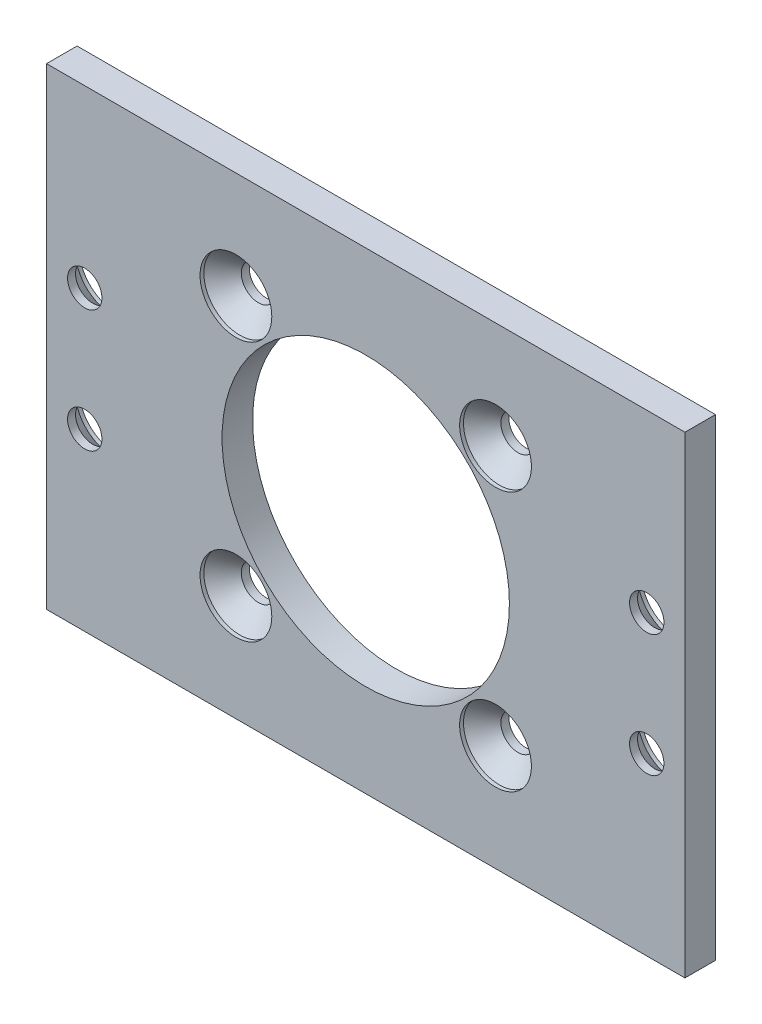
SolidWorks part; units mm, degrees
ref_plane "Plan de face" through (0, 0, 0) normal (0, 0, 1) x (1, 0, 0)
ref_plane "Plan de dessus" through (0, 0, 0) normal (0, 1, 0) x (1, 0, 0)
ref_plane "Plan de droite" through (0, 0, 0) normal (1, 0, 0) x (0, 0, -1)
sketch "Esquisse1" plane through (0, 0, 0) normal (0, 0, 1) x (1, 0, 0)
  line L0 (41.8, -30.95) -> (-41.8, -30.95)
  line L1 (41.8, -30.95) -> (41.8, 30.95)
  line L2 (-41.8, -30.95) -> (-41.8, 30.95)
  line L3 (41.8, 30.95) -> (-41.8, 30.95)
  line L4 (41.8, -30.95) -> (-41.8, 30.95) construction
  circle A0 centre (0, 0) radius 18.8138
  point P7 (0, 0)
  dimension "D1" = 83.6
  dimension "D2" = 61.9
extrude "Boss.-Extru.1" add sketch "Esquisse1" along normal blind 4
sketch "Esquisse2" plane through (0, 0, 4) normal (0, 0, 1) x (1, 0, 0)
  line L0 (17, -17) -> (-17, -17) construction
  line L1 (17, -17) -> (17, 17) construction
  line L2 (-17, -17) -> (-17, 17) construction
  line L3 (17, 17) -> (-17, 17) construction
  line L8 (-17, 17) -> (17, -17) construction
  point P12 (0, 0)
  dimension "D1" = 34
hole_wizard "Fraisage pour vis à tête fraisée M41" positions "Esquisse3" profile "Esquisse4" countersink size "M4" standard "Ansi Metric"
sketch "Esquisse3" plane through (0, 0, 4) normal (0, 0, 1) x (1, 0, 0)
  point P0 (-17, 17)
  point P3 (17, 17)
  point P6 (17, -17)
  point P9 (-17, -17)
sketch "Esquisse4" plane through (-17, 17, 4) normal (1, 0, 0) x (0, -1, 0)
  line L0 (0, 0) -> (0, 12.8519)
  line L1 (0, 12.8519) -> (2.25, 11.5)
  line L2 (2.25, 11.5) -> (2.25, 2.95)
  line L3 (2.25, 2.95) -> (4.7, 0.5)
  line L4 (4.7, 0.5) -> (4.7, 0)
  line L6 (4.7, 0) -> (0, 0)
  line L7 (-2.25, 2.95) -> (-4.7, 0.5) construction
  line L10 (0, 12.8519) -> (-2.25, 11.5) construction
  line L11 (0, -6.35) -> (0, 107.95) construction
  dimension "Diamètre du perçage" = 4.5
  dimension "Profondeur du perçage" = 11.5
  dimension "Diamètre du fraisage" = 9.4
  dimension "Angle du fraisage" = 90
  dimension "Angle de pointe" = 118
  dimension "Dégagement de la tête" = 0.5
sketch "Esquisse5" plane through (0, 0, 0) normal (0, 0, -1) x (-1, 0, 0)
  line L0 (36.8, 8) -> (36.8, -8) construction
  line L1 (36.8, -8) -> (-36.8, -8) construction
  line L2 (-36.8, -8) -> (-36.8, 8) construction
  line L3 (-36.8, 8) -> (36.8, 8) construction
  line L4 (36.8, 8) -> (41.8, 8) construction
  line L5 (41.8, 30.95) -> (41.8, -30.95) construction
  line L6 (-36.8, 8) -> (-41.8, 8) construction
  line L7 (-41.8, -30.95) -> (-41.8, 30.95) construction
  line L8 (41.8, 0) -> (-41.8, 0) construction
  point P12 (-36.8, 0)
  dimension "D1" = 5
  dimension "D2" = 5
  dimension "D3" = 16
hole_wizard "Fraisage pour vis à tête fraisée M42" positions "Esquisse6" profile "Esquisse8" countersink size "M4" standard "Ansi Metric"
sketch "Esquisse6" plane through (0, 0, 0) normal (0, 0, -1) x (-1, 0, 0)
  point P0 (36.8, 8)
  point P3 (36.8, -8)
  point P6 (-36.8, -8)
  point P9 (-36.8, 8)
sketch "Esquisse8" plane through (-36.8, 8, 0) normal (1, 0, 0) x (0, 1, 0)
  line L0 (0, 0) -> (0, 12.8519)
  line L1 (0, 12.8519) -> (2.25, 11.5)
  line L2 (2.25, 11.5) -> (2.25, 2.95)
  line L3 (2.25, 2.95) -> (4.7, 0.5)
  line L4 (4.7, 0.5) -> (4.7, 0)
  line L6 (4.7, 0) -> (0, 0)
  line L7 (-2.25, 2.95) -> (-4.7, 0.5) construction
  line L10 (0, 12.8519) -> (-2.25, 11.5) construction
  line L11 (0, -6.35) -> (0, 107.95) construction
  dimension "Diamètre du perçage" = 4.5
  dimension "Profondeur du perçage" = 11.5
  dimension "Diamètre du fraisage" = 9.4
  dimension "Angle du fraisage" = 90
  dimension "Angle de pointe" = 118
  dimension "Dégagement de la tête" = 0.5
